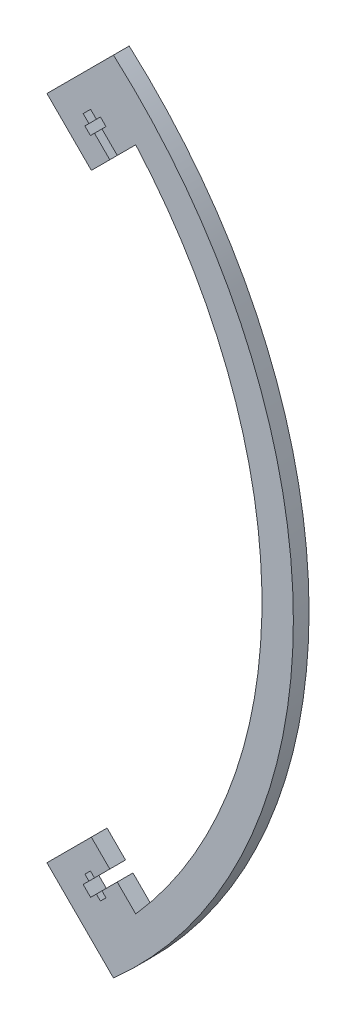
SolidWorks part; units mm, degrees
ref_plane "Front Plane" through (0, 0, 0) normal (0, 0, 1) x (1, 0, 0)
ref_plane "Top Plane" through (0, 0, 0) normal (0, 1, 0) x (1, 0, 0)
ref_plane "Right Plane" through (0, 0, 0) normal (1, 0, 0) x (0, 0, -1)
sketch "Sketch1" plane through (0, 0, 0) normal (0, 0, 1) x (1, 0, 0)
  line L0 (143.3604, 116.9193) -> (134.3442, 107.9031)
  line L1 (143.3604, -160.8213) -> (134.3442, -151.805)
  line L2 (143.3604, -160.8213) -> (128.1057, -145.5666) construction
  line L3 (128.1057, 101.6647) -> (143.3604, 116.9193) construction
  arc A0 (143.3604, 116.9193) -> (143.3604, -160.8213) centre (-21.951, -21.951) cw
  arc A1 (134.3442, 107.9031) -> (134.3442, -151.805) centre (-21.951, -21.951) cw
  arc A2 (143.3604, 116.9193) -> (131.0145, 130.4116) centre (-21.951, -21.951) ccw construction
  dimension "D1" = 12.7
extrude "Boss-Extrude1" add sketch "Sketch1" along normal blind 6.35
ref_plane "Clothes Line Center Plane" through (0, -21.951, 0) normal (0, 1, 0) x (1, 0, 0)
sketch "Sketch4" plane through (0, 0, 6.35) normal (0, 0, 1) x (1, 0, 0)
  line L0 (134.3442, -151.805) -> (143.3604, -160.8213)
  line L1 (139.4438, -165.8849) -> (130.4636, -156.9046) construction
  line L2 (105.6551, -132.0962) -> (123.6156, -150.0567) construction
  line L3 (139.194, -165.6351) -> (112.2532, -138.6943)
  line L4 (112.2532, -138.6943) -> (94.2927, -156.6548)
  line L5 (94.2927, -156.6548) -> (121.204, -183.5661)
  arc A0 (143.3604, -160.8213) -> (139.194, -165.6351) centre (-21.951, -21.951) cw
  arc A1 (134.3442, -151.805) -> (130.1981, -156.6392) centre (-21.951, -21.951) cw
  arc A2 (139.194, -165.6351) -> (121.204, -183.5661) centre (-21.951, -21.951) cw
  arc A3 (134.3442, -151.805) -> (134.3442, 107.9031) centre (-21.951, -21.951) ccw construction
  arc A4 (143.3604, -160.8213) -> (143.3604, 116.9193) centre (-21.951, -21.951) ccw construction
  arc A5 (-192.6342, 110.2612) -> (-196.6177, 104.9519) centre (-21.951, -21.951) ccw construction
  line M8 (134.3442, -151.805) -> (143.3604, -160.8213)
  dimension "D1" = 25.4
  dimension "D2" = 38.1
extrude "Boss-Extrude3" add sketch "Sketch4" against normal up to surface (6.35 mm away) contours A1 L3 A0 M8 | A2 L3 L4 L5 up to face at (163.2257, -21.951, 0)
sketch "Sketch5" plane through (0, 0, 6.35) normal (0, 0, 1) x (1, 0, 0)
  line L0 (121.2256, -147.6667) -> (103.2651, -165.6272) construction
  line L1 (130.1981, -156.6392) -> (112.2532, -138.6943) construction
  line L2 (94.2927, -156.6548) -> (121.204, -183.5661) construction
  line L3 (130.1981, -156.6392) -> (112.2376, -174.5997)
  line L4 (112.2532, -138.6943) -> (94.2927, -156.6548) construction
  line B0 (122.7343, -149.1754) -> (119.717, -146.158)
  line B1 (111.2755, -154.5995) -> (109.6411, -152.9651)
  line B2 (109.6411, -152.9651) -> (111.8862, -150.72)
  line B3 (111.8862, -150.72) -> (113.5206, -152.3544)
  line B4 (113.5206, -152.3544) -> (119.717, -146.158)
  line B5 (111.2755, -154.5995) -> (108.9406, -156.9344)
  line B6 (108.9406, -156.9344) -> (111.958, -159.9517)
  line B7 (114.2929, -157.6169) -> (111.958, -159.9517)
  line B8 (116.5379, -155.3718) -> (122.7343, -149.1754)
  line B9 (118.1723, -157.0062) -> (116.5379, -155.3718)
  line B10 (115.9273, -159.2513) -> (118.1723, -157.0062)
  line B11 (114.2929, -157.6169) -> (115.9273, -159.2513)
  line M9 (130.1981, -156.6392) -> (112.2532, -138.6943)
sketch_block_instance "TSlot-1"
sketch_block "TSlot" parameters "D1"=3.302, "D2"=3.175
extrude "Cut-Extrude1" cut sketch "Sketch5" against normal through all contours L0 B6 B7 B11 B10 B9 B8 M9 | L0 B0 B4 B3 B2 B1 B5 B6
mirror "Mirror2" about plane through (0, -21.951, 0) normal (0, 1, 0) of "Boss-Extrude3", "Cut-Extrude1"
